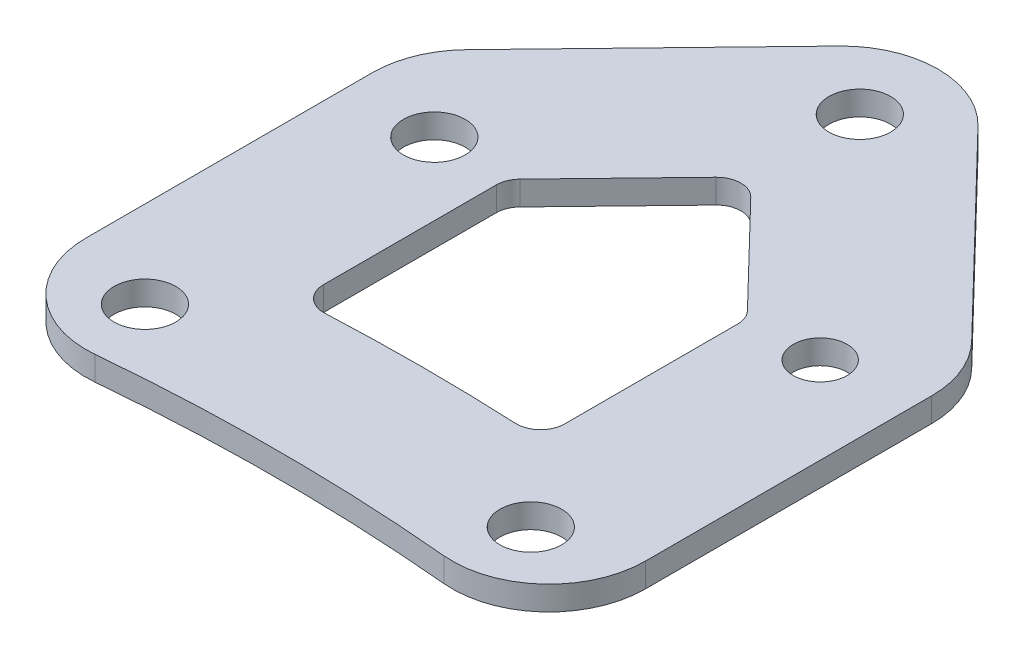
SolidWorks part; units mm, degrees
ref_plane "Front Plane" through (0, 0, 0) normal (0, 0, 1) x (1, 0, 0)
ref_plane "Top Plane" through (0, 0, 0) normal (0, 1, 0) x (1, 0, 0)
ref_plane "Right Plane" through (0, 0, 0) normal (1, 0, 0) x (0, 0, -1)
sketch "Sketch1" plane through (0, 0, 0) normal (0, 1, 0) x (1, 0, 0)
  line L1 (0, 0) -> (18.415, -19.05)
  line L2 (18.415, -19.05) -> (18.415, -47.625)
  line L4 (-18.415, -47.625) -> (-18.415, -19.05)
  line L5 (-18.415, -19.05) -> (0, 0)
  arc A0 (-18.415, -47.625) -> (18.415, -47.625) centre (0, -171.7322) cw
  point P3 (-20.7308, -14.6667)
  point P8 (0, 0)
  point P9 (0, 0)
  dimension "D2" = 125.466
  dimension "D1" = 47.625
  dimension "D3" = 36.83
  dimension "D4" = 19.05
extrude "Boss-Extrude1" add sketch "Sketch1" along normal blind 1.5875
sketch "Sketch3" plane through (0, 1.5875, 0) normal (0, 1, 0) x (1, 0, 0)
  circle A0 centre (12.7, -42.2941) radius 2.032
  circle A1 centre (-12.7, -42.2941) radius 2.032
  circle A2 centre (-12.7, -23.2441) radius 2.032
  circle A3 centre (12.7, -23.2441) radius 1.778
  circle A4 centre (0, -7.9375) radius 2.032
  point P14 (0, -7.0617)
  dimension "D1" = 4.064
  dimension "D2" = 3.556
  dimension "D3" = 7.9375
extrude "Cut-Extrude1" cut sketch "Sketch3" against normal through all
sketch "Sketch4" plane through (0, 1.5875, 0) normal (0, 1, 0) x (1, 0, 0)
  line L17 (7.9375, -47.625) -> (7.9375, -23.2863)
  line L18 (-7.9375, -23.2863) -> (-7.9375, -47.625)
  line L19 (7.9375, -23.2863) -> (0, -15.0751)
  line L20 (0, -15.0751) -> (-7.9375, -23.2863)
  line L21 (7.9375, -36.9748) -> (7.9375, -23.2863)
  line L22 (-7.9375, -23.2863) -> (-7.9375, -36.9748)
  line L23 (7.9375, -23.2863) -> (0, -15.0751)
  line L24 (0, -15.0751) -> (-7.9375, -23.2863)
  arc A2 (19.813, -38.2032) -> (-19.813, -38.2032) centre (0, -171.7322) ccw
  arc A3 (7.9375, -36.9748) -> (-7.9375, -36.9748) centre (0, -171.7322) ccw
  point P0 (0, -19.1864)
  dimension "D1" = 10.4775
  dimension "D2" = 9.525
extrude "Cut-Extrude2" cut sketch "Sketch4" against normal through all
fillet "Fillet1" radius 6.35 5 edges at (-18.415, 0.7937, 47.625) (18.415, 0.7937, 47.625) (18.415, 0.7937, 19.05) (-18.415, 0.7937, 19.05) (0, 0.7937, 0)
fillet "Fillet2" radius 1.5875 5 edges at (-7.9375, 0.7937, 36.9748) (7.9375, 0.7937, 36.9748) (7.9375, 0.7937, 23.2863) (-7.9375, 0.7937, 23.2863) (0, 0.7937, 15.0751)
